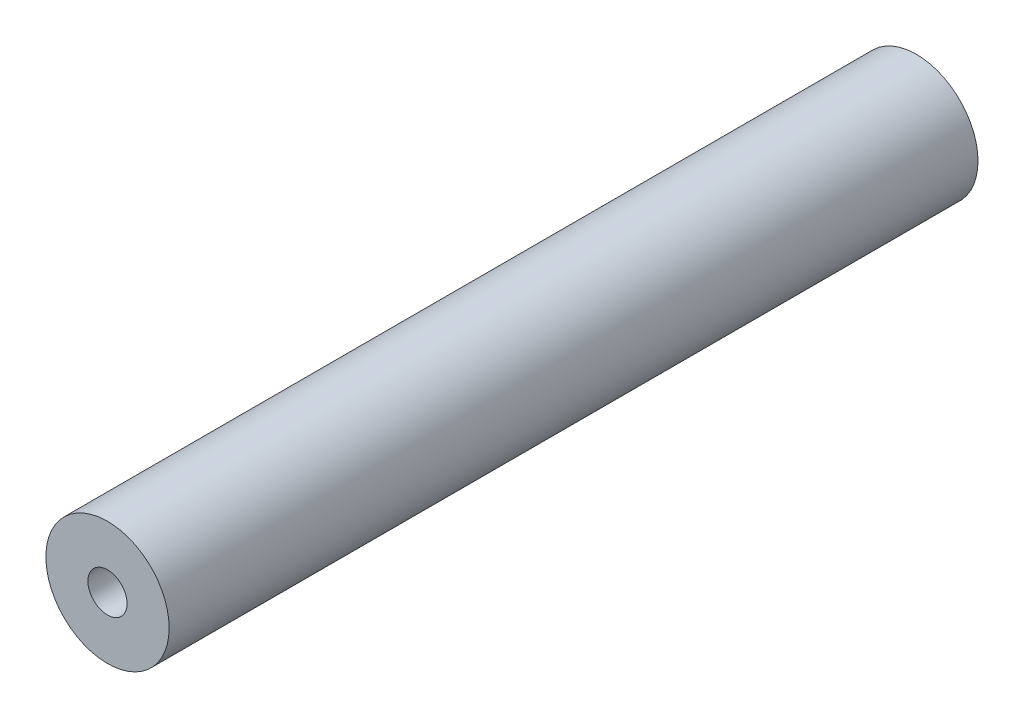
SolidWorks part; units mm, degrees
material "6061-T6 (SS)"
ref_plane "Front Plane" through (0, 0, 0) normal (0, 0, 1) x (1, 0, 0)
ref_plane "Top Plane" through (0, 0, 0) normal (0, 1, 0) x (1, 0, 0)
ref_plane "Right Plane" through (0, 0, 0) normal (1, 0, 0) x (0, 0, -1)
sketch "Sketch1" plane through (0, 0, 0) normal (0, 0, 1) x (1, 0, 0)
  circle A1 centre (0, 0) radius 6.35
  dimension "D2" = 12.7
extrude "Boss-Extrude1" add sketch "Sketch1" along normal mid plane 83.345
hole_wizard "#10-32 Tapped Hole1" positions "3DSketch1" profile "Sketch2" tap size "#10-32" standard "ANSI Inch"
sketch3d "3DSketch1"
  line L0 (0, 0, 41.6725) -> (0, 0, -41.6725) construction
  point P0 (0, 0, -41.6725)
  point P4 (0, 0, 41.6725)
sketch "Sketch2" plane through (0, 0, -41.6725) normal (1, 0, 0) x (0, 1, 0)
  line L0 (0, 0) -> (0, 13.2428)
  line L1 (0, 13.2428) -> (2.0193, 12.0294)
  line L2 (2.0193, 12.0294) -> (2.0193, 0)
  line L5 (2.0193, 0) -> (0, 0)
  line L10 (0, 13.2428) -> (-2.0193, 12.0294) construction
  line L11 (0, -6.35) -> (0, 107.95) construction
  dimension "Tap Drill Dia." = 4.0386
  dimension "Tap Drill Depth" = 12.0294
  dimension "Drill Angle" = 118
cosmetic thread "Hole Thread1"
cosmetic thread "Hole Thread2"
